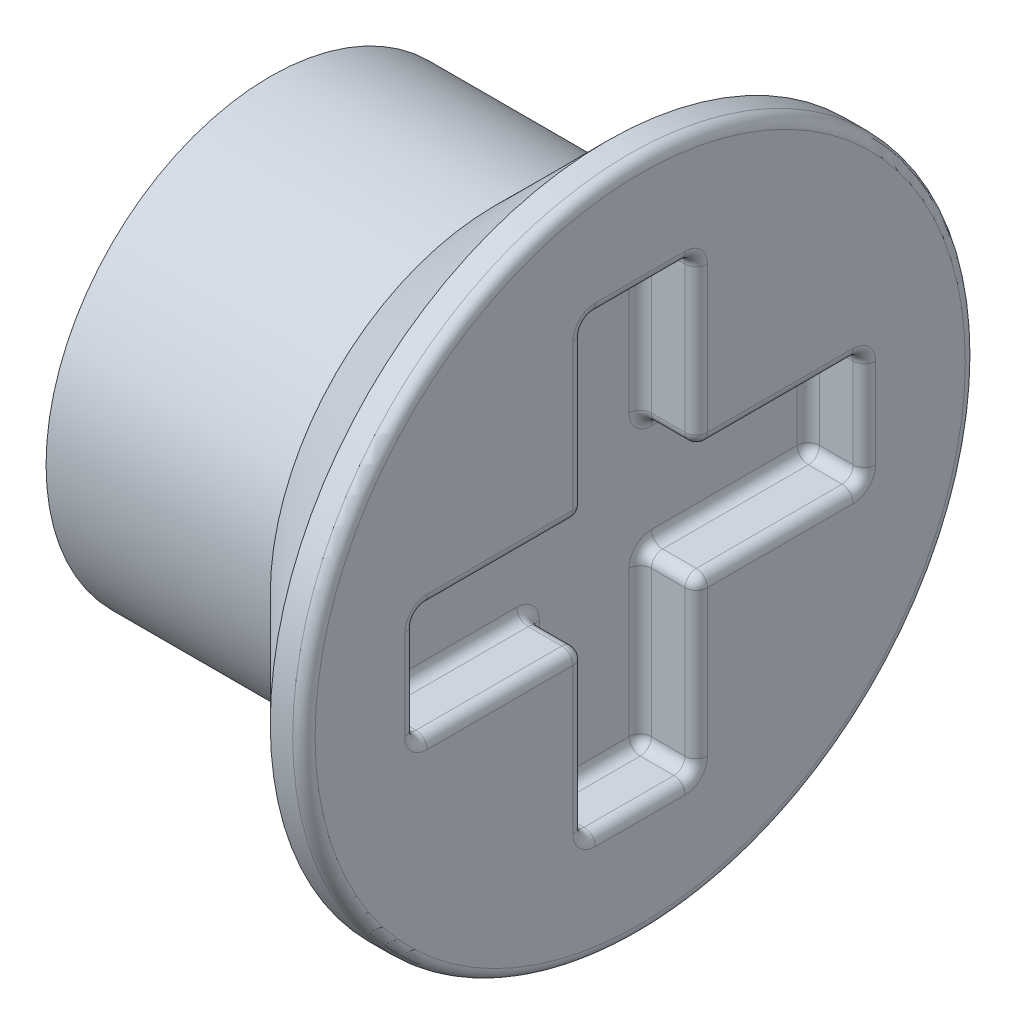
SolidWorks part; units mm, degrees
material "moto_black"
ref_plane "Front Plane" through (0, 0, 0) normal (0, 0, 1) x (1, 0, 0)
ref_plane "Top Plane" through (0, 0, 0) normal (0, 1, 0) x (1, 0, 0)
ref_plane "Right Plane" through (0, 0, 0) normal (1, 0, 0) x (0, 0, -1)
sketch "Sketch1" plane through (0, 0, 0) normal (1, 0, 0) x (0, 0, -1)
  circle A0 centre (0, 0) radius 3
  dimension "D1" = 6
extrude "Boss-Extrude1" add sketch "Sketch1" along normal blind 1.3
chamfer "Chamfer1" distance 1 angle 45 1 edges at (0, 0, -3)
sketch "Sketch2" plane through (0, 0, 0) normal (-1, 0, 0) x (0, 0, 1)
  circle A2 centre (0, 0) radius 2
  circle A3 centre (0, 0) radius 2
  dimension "D1" = 0
extrude "Boss-Extrude2" add sketch "Sketch2" along normal blind 2
sketch "Sketch3" plane through (1.3, 0, 0) normal (1, 0, 0) x (0, 0, -1)
  line L1 (-2, -0.5) -> (2, -0.5)
  line L2 (-2, -0.5) -> (-2, 0.5)
  line L3 (-2, 0.5) -> (2, 0.5)
  line L4 (2, -0.5) -> (2, 0.5)
  line L5 (-2, -0.5) -> (2, 0.5) construction
  line L6 (-2, 0.5) -> (2, -0.5) construction
  line L7 (-0.5, -2) -> (0.5, -2)
  line L8 (-0.5, -2) -> (-0.5, 2)
  line L9 (-0.5, 2) -> (0.5, 2)
  line L10 (0.5, -2) -> (0.5, 2)
  line L11 (-0.5, -2) -> (0.5, 2) construction
  line L12 (-0.5, 2) -> (0.5, -2) construction
  circle A2 centre (0, 0) radius 3
  circle A3 centre (0, 0) radius 3
  dimension "D2" = 4
  dimension "D3" = 1
  dimension "D4" = 4
  dimension "D5" = 1
  dimension "D1" = 0
extrude "Cut-Extrude1" cut sketch "Sketch3" against normal blind 0.5 contours L3 L10 L9 L8 | L1 L10 L3 L8 | L7 L10 L1 L8 | L1 L8 L3 L2 | L10 L1 L4 L3
fillet "Fillet1" radius 0.1 37 edges at (1.05, 0.5, 2) (1.05, 2, 0.5) (1.05, 0.5, 0.5) (1.3, 2, 0) (0.8, 2, 0) (1.3, 0, -2) (0.8, 0, -2) (1.3, -2, 0) (0.8, -2, 0) (1.3, 0, 2) (0.8, 0, 2) (1.3, 0.5, 1.25) (0.8, 0.5, 1.25) (1.3, 1.25, 0.5) (0.8, 1.25, 0.5) (1.05, -0.5, 2) (1.3, -0.5, 1.25) (0.8, -0.5, 1.25) (1.05, -0.5, 0.5) (1.3, -1.25, 0.5) (0.8, -1.25, 0.5) (1.05, -2, 0.5) (1.05, -2, -0.5) (1.3, -1.25, -0.5) (0.8, -1.25, -0.5) (1.05, -0.5, -0.5) (1.3, -0.5, -1.25) (0.8, -0.5, -1.25) (1.05, -0.5, -2) (1.05, 0.5, -2) (1.3, 0.5, -1.25) (0.8, 0.5, -1.25) (1.05, 0.5, -0.5) (1.3, 1.25, -0.5) (0.8, 1.25, -0.5) (1.05, 2, -0.5) (1.3, 0, -3)
